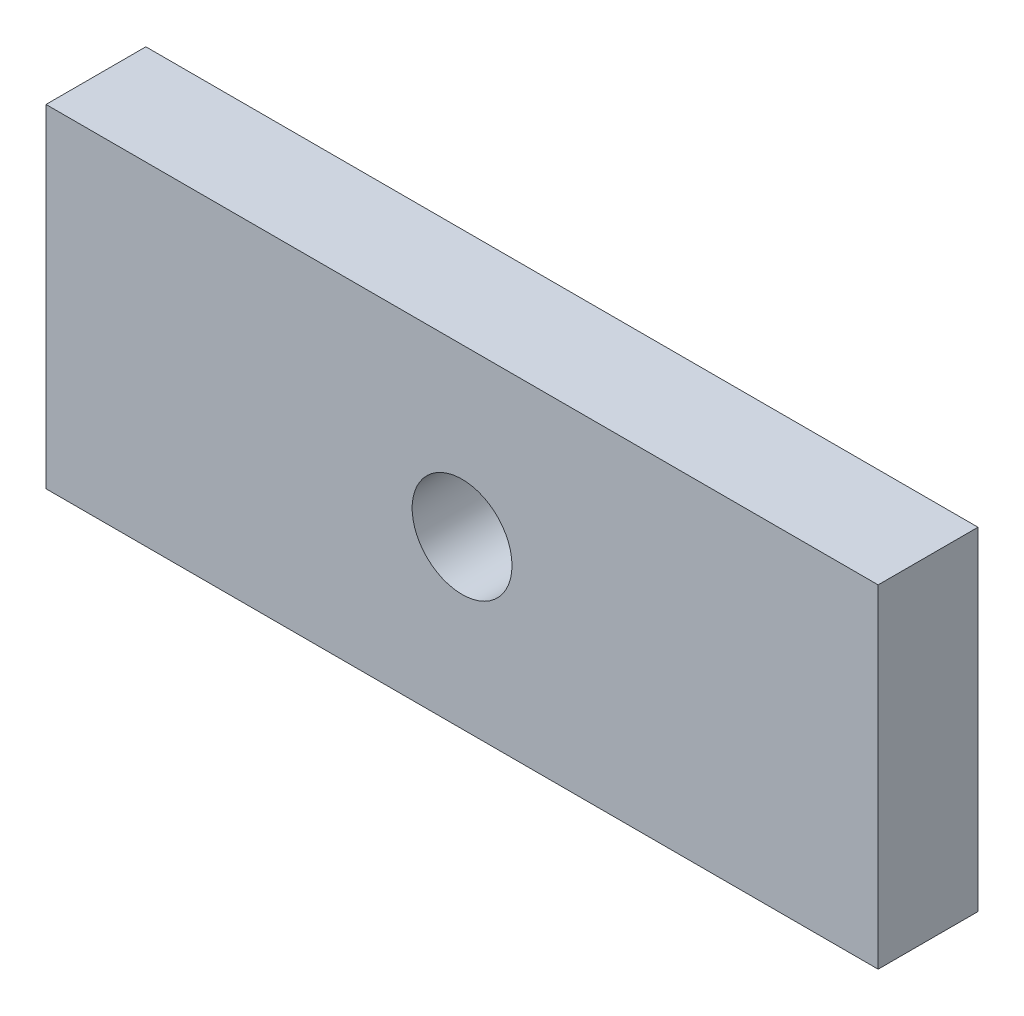
SolidWorks part; units mm, degrees
ref_plane "前视基准面" through (0, 0, 0) normal (0, 0, 1) x (1, 0, 0)
ref_plane "上视基准面" through (0, 0, 0) normal (0, 1, 0) x (1, 0, 0)
ref_plane "右视基准面" through (0, 0, 0) normal (1, 0, 0) x (0, 0, -1)
sketch "edrawing1" plane through (0, 0, 0) normal (0, 0, 1) x (1, 0, 0)
  line L1 (0, 0) -> (25, 0)
  line L2 (0, 0) -> (0, 10)
  line L3 (0, 10) -> (25, 10)
  line L4 (25, 0) -> (25, 10)
  circle A0 centre (12.5, 5) radius 1.5
  point P7 (12.0864, 4.9773)
  dimension "DS_D3" = 3
  dimension "DS_D1" = 25
  dimension "DS_D2" = 10
  dimension "DS_D4" = 5
  dimension "DS_D5" = 12.5
extrude "extrude" add sketch "edrawing1" along normal blind 3
